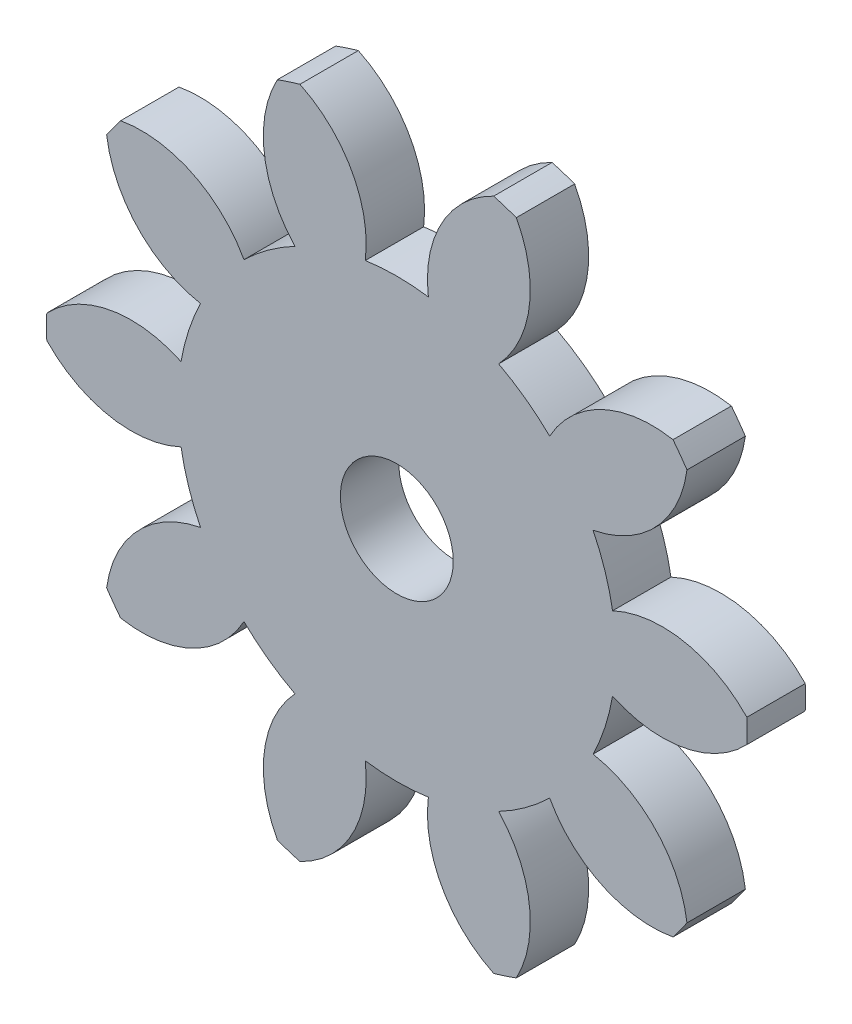
SolidWorks part; units mm, degrees
ref_plane "Front Plane" through (0, 0, 0) normal (0, 0, 1) x (1, 0, 0)
ref_plane "Top Plane" through (0, 0, 0) normal (0, 1, 0) x (1, 0, 0)
ref_plane "Right Plane" through (0, 0, 0) normal (1, 0, 0) x (0, 0, -1)
sketch "Sketch1" plane through (0, 0, 0) normal (0, 0, 1) x (1, 0, 0)
  circle A0 centre (0, 0) radius 18
  dimension "addendumDiameter" = 36
extrude "Boss-Extrude1" add sketch "Sketch1" along normal blind 3
sketch "Sketch2" plane through (0, 0, 3) normal (0, 0, 1) x (1, 0, 0)
  line L0 (0, 0) -> (0, 34.174) construction
  line L1 (0, 0) -> (-6.2457, 19.2224) construction
  line L2 (-2.3368, 14.8169) -> (-4.5777, 14.0888) construction
  circle A0 centre (0, 0) radius 14.0954 construction
  circle A1 centre (0, 0) radius 15 construction
  circle A2 centre (0, 0) radius 11.25 construction
  arc A3 (-4.9785, 17.2978) -> (-1.6211, 11.1326) centre (-7.5734, 11.888) cw
  circle A4 centre (0, 0) radius 18 construction
  arc A5 (4.9785, 17.2978) -> (1.6211, 11.1326) centre (7.5734, 11.888) ccw
  arc A6 (-4.9785, 17.2978) -> (4.9785, 17.2978) centre (0, 0) cw
  arc A7 (1.6211, 11.1326) -> (-1.6211, 11.1326) centre (0, 0) ccw
  circle M3 centre (0, 0) radius 18
  dimension "dedendum_circle" = 22.5
  dimension "Base_diameter" = 28.1908
  dimension "D1" = 30
  dimension "D4" = 6
  dimension "D2" = 18
  dimension "D5" = 2.3562
extrude "Cut-Extrude2" cut sketch "Sketch2" against normal up to surface (3 mm away) contours A7 A5 A3 M3
pattern_circular "CirPattern1" count 10 over 360 about axis through (0, 0, 0) along (0, 0, 1) of "Cut-Extrude2"
sketch "Sketch3" plane through (0, 0, 3) normal (0, 0, 1) x (1, 0, 0)
  line L0 (0, 0) -> (0, 25.7954) construction
  line L4 (0, 3) -> (4.0415, 10)
  line L5 (4.0415, 10) -> (-4.0415, 10)
  line L6 (-4.0415, 10) -> (0, 3)
  dimension "D1" = 10
  dimension "D2" = 3
  dimension "D3" = 60
extrude "Cut-Extrude3" [suppressed] cut sketch "Sketch3" against normal through all
fillet "Fillet1" [suppressed] radius 1
pattern_circular "CirPattern2" [suppressed] count 6 over 360
sketch "Sketch5" plane through (0, 0, 3) normal (0, 0, 1) x (1, 0, 0)
  circle A1 centre (0, 0) radius 2.9
  dimension "D1" = 5.8
extrude "Cut-Extrude4" cut sketch "Sketch5" against normal through all
equation "\"module\" = 3"
equation "\"teeth\" = 10"
equation "\"pressureAngle\"= 20deg"
equation "\"gearThickness\"= 3"
equation "\"addendumFactor\"= 1"
equation "\"dedendumFactor\"= 1.25"
equation "\"pitch\"= 1 / \"module\""
equation "\"pitchDiameter\"= \"teeth\" / \"pitch\""
equation "\"addendum\"= \"addendumFactor\" / \"pitch\""
equation "\"dedendum\"= \"dedendumFactor\" / \"pitch\""
equation "\"addendumDiameter@Sketch1\"=\"pitchDiameter\" + 2 * \"addendum\""
equation "\"D1@Boss-Extrude1\"=\"gearThickness\""
equation "\"dedendum_circle@Sketch2\" = \"pitchDiameter\" - 2 * \"dedendum\""
equation "\"Base_diameter@Sketch2\"=\"pitchDiameter\" * cos ( \"pressureAngle\" )"
equation "\"D1@Sketch2\"=\"pitchDiameter\""
equation "\"D2@Sketch2\"=180/\"teeth\""
equation "\"D4@Sketch2\"=\"pitchDiameter\"/5"
equation "\"D5@Sketch2\"=PI/2/\"pitch\"/2"
equation "\"D1@CirPattern1\"=\"teeth\""
